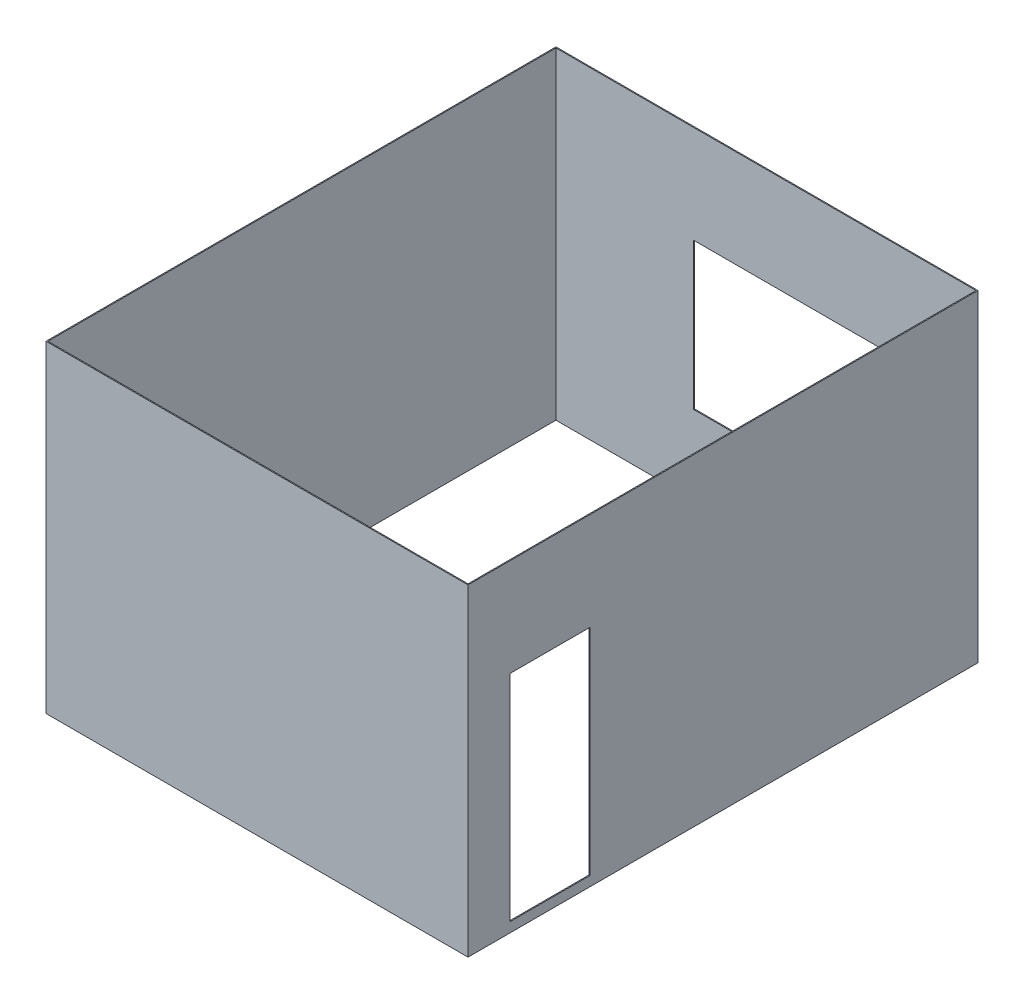
SolidWorks part; units mm, degrees
ref_plane "Спереди" through (0, 0, 0) normal (0, 0, 1) x (1, 0, 0)
ref_plane "Сверху" through (0, 0, 0) normal (0, 1, 0) x (1, 0, 0)
ref_plane "Справа" through (0, 0, 0) normal (1, 0, 0) x (0, 0, -1)
sketch "Эскиз1" plane through (0, 0, 0) normal (0, 1, 0) x (1, 0, 0)
  line L1 (0, 0) -> (-430, 0)
  line L2 (0, 0) -> (0, 520)
  line L3 (0, 520) -> (-430, 520)
  line L4 (-430, 0) -> (-430, 520)
  dimension "D1" = 520
  dimension "D2" = 430
extrude "Вытянуть-Тонкостенный2" add sketch "Эскиз1" along normal blind 330 thin thin type one direction wall 1
sketch "Эскиз2" plane through (1, 0, 0) normal (1, 0, 0) x (0, 0, -1)
  line L0 (-1, 0) -> (521, 0) construction
  line L1 (42, 10) -> (124, 10)
  line L2 (42, 10) -> (42, 230)
  line L3 (42, 230) -> (124, 230)
  line L4 (124, 10) -> (124, 230)
  line L5 (-1, 330) -> (-1, 0) construction
  dimension "D1" = 10
  dimension "D2" = 220
  dimension "D3" = 82
  dimension "D4" = 43
extrude "Вырез-Вытянуть2" cut sketch "Эскиз2" against normal blind 10
sketch "Эскиз3" plane through (0, 0, -521) normal (0, 0, -1) x (-1, 0, 0)
  line L0 (-1, 330) -> (-1, 0) construction
  line L1 (289, 80) -> (89, 80)
  line L2 (289, 80) -> (289, 230)
  line L3 (289, 230) -> (89, 230)
  line L4 (89, 80) -> (89, 230)
  line L5 (-1, 0) -> (431, 0) construction
  dimension "D1" = 200
  dimension "D2" = 150
  dimension "D3" = 90
  dimension "D4" = 80
extrude "Вырез-Вытянуть3" cut sketch "Эскиз3" against normal blind 10
